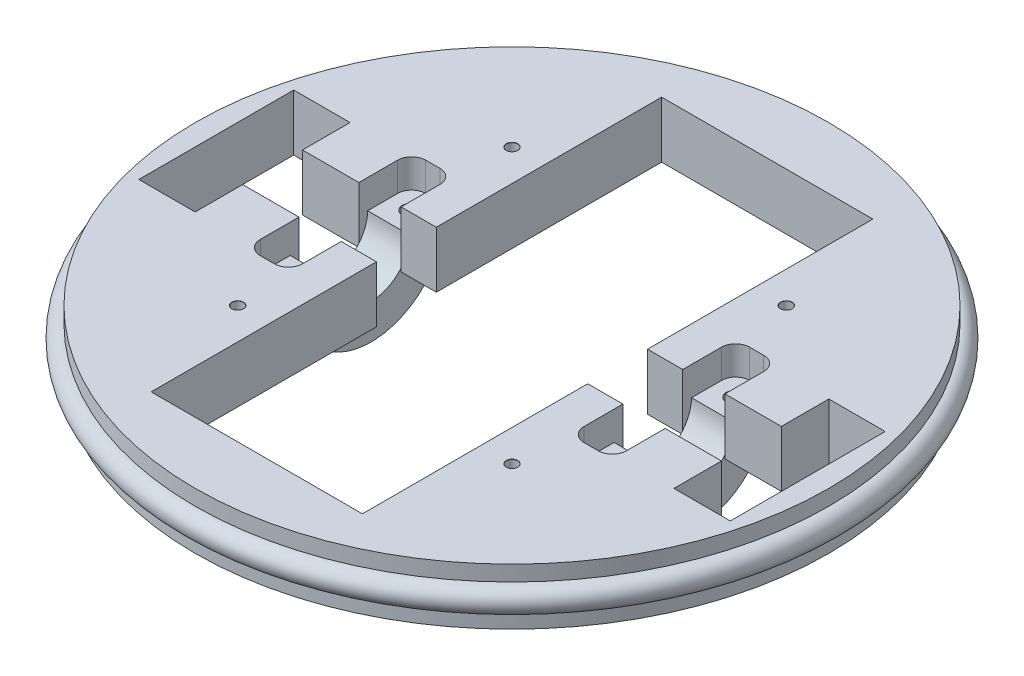
SolidWorks part; units mm, degrees
ref_plane "Front Plane" through (0, 0, 0) normal (0, 0, 1) x (1, 0, 0)
ref_plane "Top Plane" through (0, 0, 0) normal (0, 1, 0) x (1, 0, 0)
ref_plane "Right Plane" through (0, 0, 0) normal (1, 0, 0) x (0, 0, -1)
sketch "Sketch1" plane through (0, 0, 0) normal (0, 1, 0) x (1, 0, 0)
  line L0 (-15, -36.25) -> (-15, -4.25)
  line L1 (-12.5, -33.75) -> (12.5, -33.75) construction
  line L2 (-12.5, -33.75) -> (-12.5, 33.75) construction
  line L3 (-12.5, 33.75) -> (12.5, 33.75) construction
  line L4 (12.5, -33.75) -> (12.5, 33.75) construction
  line L5 (-12.5, -33.75) -> (12.5, 33.75) construction
  line L6 (-12.5, 33.75) -> (12.5, -33.75) construction
  line L7 (-15, 36.25) -> (15, 36.25)
  line L9 (-15, -36.25) -> (15, -36.25)
  line L10 (-15, 4.25) -> (-15, 36.25)
  line L15 (-42, -11) -> (42, 11) construction
  line L16 (-42, 11) -> (42, -11) construction
  line L17 (-15, -36.25) -> (-15, 36.25) construction
  line L21 (15, -36.25) -> (15, 36.25) construction
  line L22 (-45, 0) -> (45, 0) construction
  line L25 (-15, 4.25) -> (-20, 4.25)
  line L26 (-20, 5.75) -> (-20, 4.25)
  line L27 (0, 45) -> (0, -45) construction
  line L28 (-20, -5.75) -> (-20, -4.25)
  line L29 (-15, -4.25) -> (-20, -4.25)
  line L30 (15, -36.25) -> (15, -4.25)
  line L31 (15, 4.25) -> (15, 36.25)
  line L32 (15, 4.25) -> (20, 4.25)
  line L33 (15, -4.25) -> (20, -4.25)
  line L34 (20, -5.75) -> (20, -4.25)
  line L35 (20, 5.75) -> (20, 4.25)
  line L36 (-26, 5.75) -> (-26, 4.25)
  line L37 (-26, 4.25) -> (-34, 4.25)
  line L38 (-42, 4.25) -> (-42, 11) construction
  line L39 (-26, 5.75) -> (-20, 5.75)
  line L41 (-26, -5.75) -> (-26, -4.25)
  line L42 (-26, -4.25) -> (-34, -4.25)
  line L43 (-42, -4.25) -> (-42, -11) construction
  line L45 (-20, -5.75) -> (-26, -5.75)
  line L46 (26, 5.75) -> (26, 4.25)
  line L47 (26, 5.75) -> (20, 5.75)
  line L48 (20, -5.75) -> (26, -5.75)
  line L49 (26, -5.75) -> (26, -4.25)
  line L53 (-34, 4.25) -> (-34, 11)
  line L54 (-42, -11) -> (-34, -11)
  line L55 (-42, -11) -> (-42, 11)
  line L56 (-42, 11) -> (-34, 11)
  line L57 (-34, -11) -> (-34, -4.25)
  line L58 (26, -4.25) -> (34, -4.25)
  line L59 (26, 4.25) -> (34, 4.25)
  line L60 (34, 4.25) -> (34, 11)
  line L61 (34, -11) -> (34, -4.25)
  line L62 (42, -11) -> (34, -11)
  line L63 (42, 11) -> (34, 11)
  line L64 (42, -11) -> (42, 11)
  circle A0 centre (0, 0) radius 45
  dimension "D1" = 90
  dimension "D2" = 25
  dimension "D3" = 67.5
  dimension "D5" = 22
  dimension "D6" = 84
  dimension "D7" = 5
  dimension "D8" = 8.5
  dimension "D9" = 6
  dimension "D10" = 11.5
  dimension "D11" = 8
  dimension "D4" = 2.5
extrude "Boss-Extrude1" add sketch "Sketch1" along normal blind 8
sketch "Sketch3" plane through (0, 0, 0) normal (0, 0, 1) x (1, 0, 0)
  line L0 (-45, 8) -> (-45, 0) construction
  line L1 (-45, 5.8) -> (-45, 2.2)
  arc A0 (-45, 5.8) -> (-45, 2.2) centre (-45, 4) ccw
  dimension "D1" = 1.8
ref_axis "Axis1" through (0, 8.4, 0) along (0, -1, 0)
revolve "Revolve1" add sketch "Sketch3" angle 360 about axis through (0, 8.4, 0) along (0, -1, 0)
sketch "Sketch2" plane through (0, 8, 0) normal (0, 1, 0) x (1, 0, 0)
  line L0 (-31.8198, 31.8198) -> (31.8198, -31.8198) construction
  line L1 (-31.8198, -31.8198) -> (31.8198, 31.8198) construction
  circle A1 centre (0, 0) radius 45 construction
  circle A2 centre (0, 0) radius 50 construction
  point P6 (0, 0)
  point P9 (0, 0)
  point P13 (-35.3553, 35.3553)
  point P14 (-19.4808, 19.4808)
  point P15 (19.4808, 19.4808)
  point P16 (19.4808, -19.4808)
  point P17 (-19.4808, -19.4808)
  point P18 (0, 0)
  point P22 (0, 0)
  dimension "D1" = 22.45
  dimension "D2" = 100
  dimension "D3" = 4
hole_wizard "Tap Drill for M2x0.4 Tap1" positions "Sketch6" profile "Sketch5" hole size "M2x0.4" standard "ANSI Metric" end condition through all
sketch "Sketch6" plane through (0, 8, 0) normal (0, 1, 0) x (1, 0, 0)
  point P0 (-19.4808, 19.4808)
  point P3 (19.4808, 19.4808)
  point P6 (19.4808, -19.4808)
  point P9 (-19.4808, -19.4808)
sketch "Sketch5" plane through (-19.4808, 8, -19.4808) normal (1, 0, 0) x (0, 0, 1)
  line L0 (0, 0) -> (0, 8)
  line L1 (0, 8) -> (0.8, 8)
  line L2 (0.8, 8) -> (0.8, 0.025)
  line L3 (0.8, 0.025) -> (0.825, 0)
  line L5 (0.825, 0) -> (0, 0)
  line L6 (-0.8, 0.025) -> (-0.825, 0) construction
  line L11 (0, -6.35) -> (0, 107.95) construction
  dimension "Thru Hole Dia." = 1.6
  dimension "Thru Hole Depth" = 8
  dimension "Near C'Sink Dia." = 1.65
  dimension "Near C'Sink Angle" = 90
sketch "Sketch7" plane through (0, 8, 0) normal (0, 1, 0) x (1, 0, 0)
  line L0 (-20, -5.75) -> (-20, -4.25) construction
  line L1 (-26, 11.75) -> (-20, 11.75)
  line L2 (-26, 11.75) -> (-26, -11.75)
  line L3 (-26, -11.75) -> (-20, -11.75)
  line L4 (-20, 11.75) -> (-20, -11.75)
  line L5 (-26, 5.75) -> (-26, 4.25) construction
  line L6 (-4.4, 0) -> (4.4, 0) construction
  line L8 (-23, -5.75) -> (-23, -11.75) construction
  line L9 (-26, -5.75) -> (-20, -5.75) construction
  point P8 (-26, 0)
extrude "Cut-Extrude1" cut sketch "Sketch7" against normal blind 4.1
fillet "Fillet1" radius 2 4 edges at (-26, 5.95, 11.75) (-20, 5.95, 11.75) (-20, 5.95, -11.75) (-26, 5.95, -11.75)
sketch "Sketch8" plane through (-20, 0, 0) normal (-1, 0, 0) x (0, 0, 1)
  line L0 (-4.25, 8) -> (-4.25, 0) construction
  line L1 (0, -4.4) -> (0, 4.4) construction
  line L9 (-5.4991, 3.9) -> (-10.4991, 3.9)
  line L10 (-5.75, 3.9) -> (-9.75, 3.9) construction
  line L12 (5.4991, 3.9) -> (10.4991, 3.9)
  line L13 (9.75, 3.9) -> (5.75, 3.9) construction
  arc A0 (-5.4991, 3.9) -> (5.4991, 3.9) centre (0, 4) ccw
  arc A1 (-10.4991, 3.9) -> (10.4991, 3.9) centre (0, 4) ccw
  point P5 (-4.25, 4)
  dimension "D1" = 11
  dimension "D2" = 5
extrude "Boss-Extrude2" add sketch "Sketch8" along normal up to surface (6 mm away) up to face at (-26, 3.9667, -6.5833)
hole_wizard "M2 Clearance Hole3" positions "Sketch16" profile "Sketch15" hole size "M2" standard "ANSI Metric" end condition through all
sketch "Sketch16" plane through (0, 3.9, 0) normal (0, 1, 0) x (1, 0, 0)
  line L0 (-23, -5.4991) -> (-23, -11.75) construction
  line L1 (-26, -5.4991) -> (-20, -5.4991) construction
  line L2 (-24, -11.75) -> (-22, -11.75) construction
  line L4 (-26, -8.6245) -> (-20, -8.6245) construction
  line L5 (-26, -4.25) -> (-26, -9.75) construction
  line L6 (-20, -9.75) -> (-20, -5.4991) construction
  line L7 (-4.4, 0) -> (4.4, 0) construction
  point P17 (-23, -8.6245)
  point P21 (-23, 8.6245)
sketch "Sketch15" plane through (-23, 3.9, -8.6245) normal (1, 0, 0) x (0, 0, 1)
  line L0 (0, 0) -> (0, 10.3996)
  line L1 (0, 10.3996) -> (1.2, 10.3996)
  line L2 (1.2, 10.3996) -> (1.2, 0)
  line L5 (1.2, 0) -> (0, 0)
  line L11 (0, -6.35) -> (0, 107.95) construction
  dimension "Thru Hole Dia." = 2.4
  dimension "Thru Hole Depth" = 10.3996
sketch "Sketch17" plane through (0, 0, 0) normal (0, -1, 0) x (1, 0, 0)
  circle A0 centre (-23, -8.6245) radius 1.75
  circle A1 centre (-23, 8.6245) radius 1.75
  dimension "D1" = 3.5
extrude "Cut-Extrude2" cut sketch "Sketch17" along normal through all
mirror "Mirror1" about plane through (0, 0, 0) normal (1, 0, 0) of "Cut-Extrude2", "Fillet1", "Cut-Extrude1", "Boss-Extrude2", "M2 Clearance Hole3"
